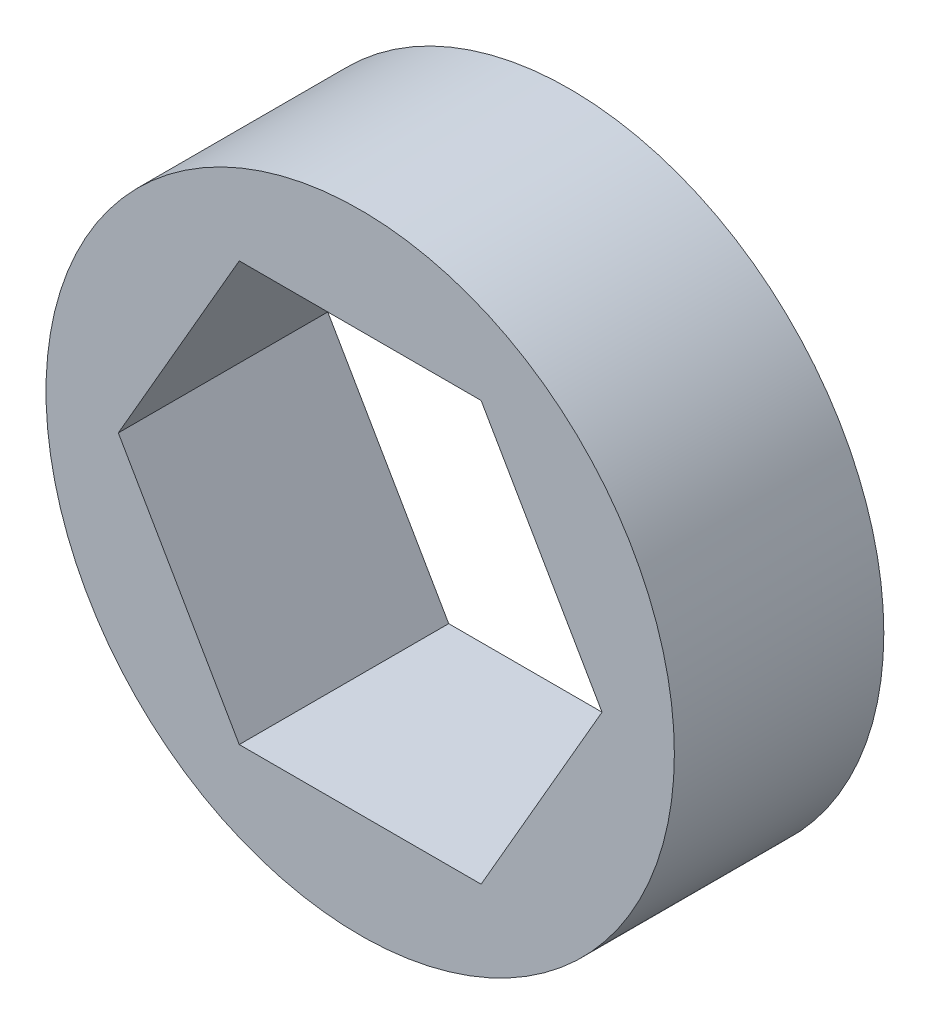
SolidWorks part; units mm, degrees
material "Nylon 101"
ref_plane "Front Plane" through (0, 0, 0) normal (0, 0, 1) x (1, 0, 0)
ref_plane "Top Plane" through (0, 0, 0) normal (0, 1, 0) x (1, 0, 0)
ref_plane "Right Plane" through (0, 0, 0) normal (1, 0, 0) x (0, 0, -1)
sketch "Sketch1" plane through (0, 0, 0) normal (0, 0, 1) x (1, 0, 0)
  line L1 (-3.6662, 6.35) -> (-7.3323, 0)
  line L2 (-7.3323, 0) -> (-3.6662, -6.35)
  line L3 (-3.6662, -6.35) -> (3.6662, -6.35)
  line L4 (3.6662, -6.35) -> (7.3323, 0)
  line L5 (7.3323, 0) -> (3.6662, 6.35)
  line L6 (3.6662, 6.35) -> (-3.6662, 6.35)
  circle A0 centre (0, 0) radius 6.35 construction
  circle A1 centre (0, 0) radius 9.525
  point P10 (0, 6.35)
  dimension "D1" = 12.7
  dimension "D2" = 19.05
extrude "Boss-Extrude1" add sketch "Sketch1" along normal blind 6.35
